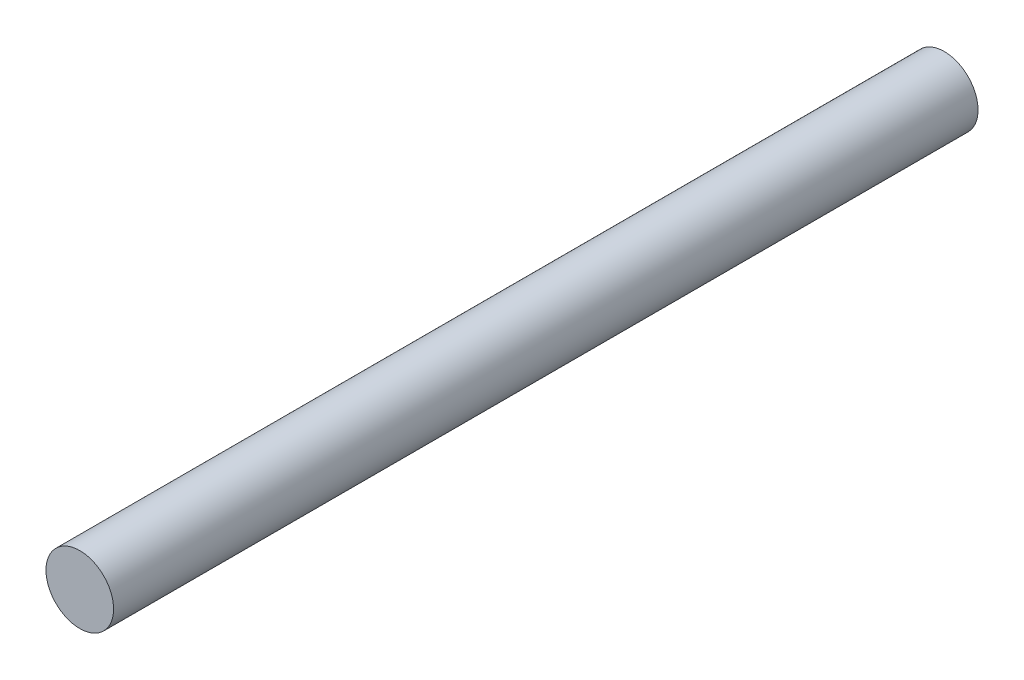
SolidWorks part; units mm, degrees
material "Ammonium Perchloride"
ref_plane "Front Plane" through (0, 0, 0) normal (0, 0, 1) x (1, 0, 0)
ref_plane "Top Plane" through (0, 0, 0) normal (0, 1, 0) x (1, 0, 0)
ref_plane "Right Plane" through (0, 0, 0) normal (1, 0, 0) x (0, 0, -1)
sketch "Sketch1" plane through (0, 0, 0) normal (0, 0, 1) x (1, 0, 0)
  circle A0 centre (0, 0) radius 47.6631
  dimension "D1" = 95.3262
extrude "Boss-Extrude1" add sketch "Sketch1" along normal blind 1219.2
